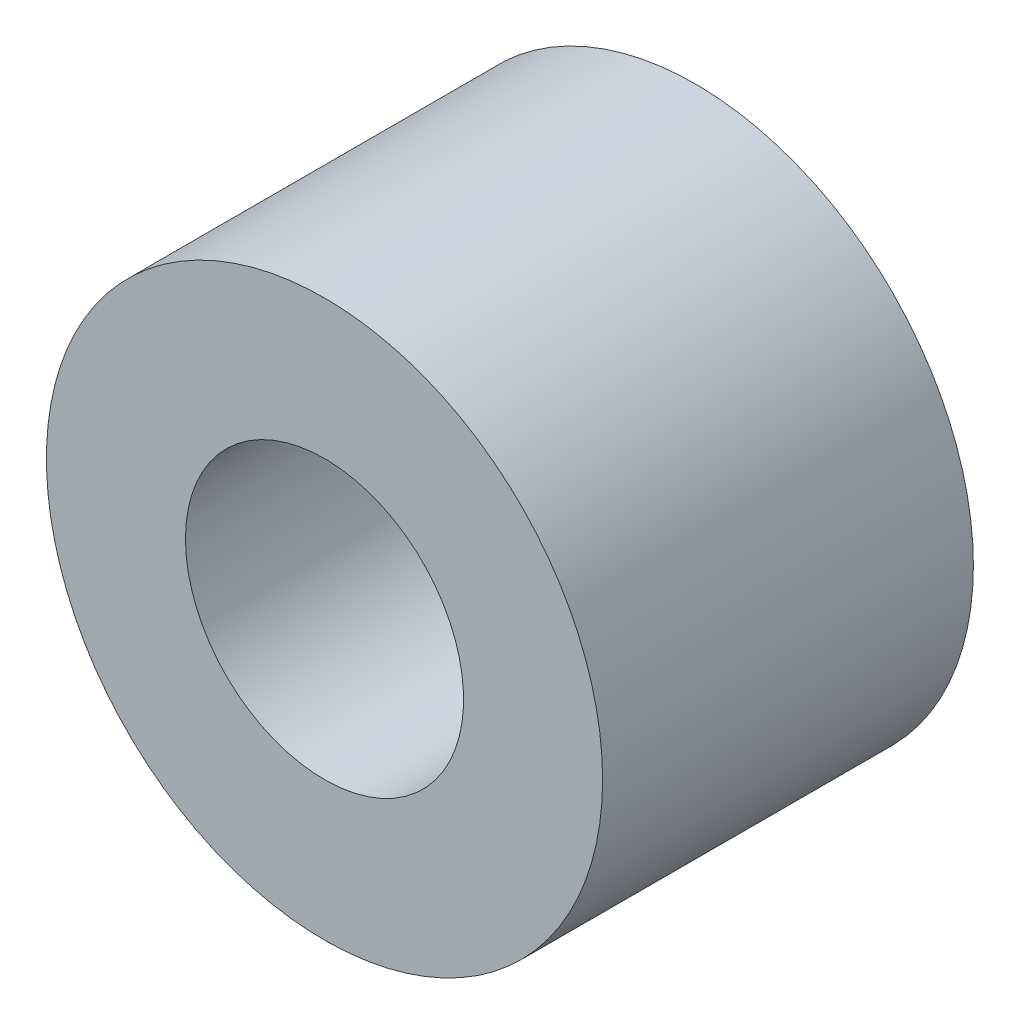
SolidWorks part; units mm, degrees
ref_plane "Plan de face" through (0, 0, 0) normal (0, 0, 1) x (1, 0, 0)
ref_plane "Plan de dessus" through (0, 0, 0) normal (0, 1, 0) x (1, 0, 0)
ref_plane "Plan de droite" through (0, 0, 0) normal (1, 0, 0) x (0, 0, -1)
sketch "Esquisse1" plane through (0, 0, 0) normal (0, 0, 1) x (1, 0, 0)
  circle A0 centre (0, 0) radius 3
  dimension "D1" = 6
extrude "Boss.-Extru.1" add sketch "Esquisse1" along normal blind 4
sketch "Esquisse2" plane through (0, 0, 0) normal (0, 0, -1) x (-1, 0, 0)
  circle A0 centre (0, 0) radius 1.5
extrude "Enlèv. mat.-Extru.1" cut sketch "Esquisse2" against normal blind 4
